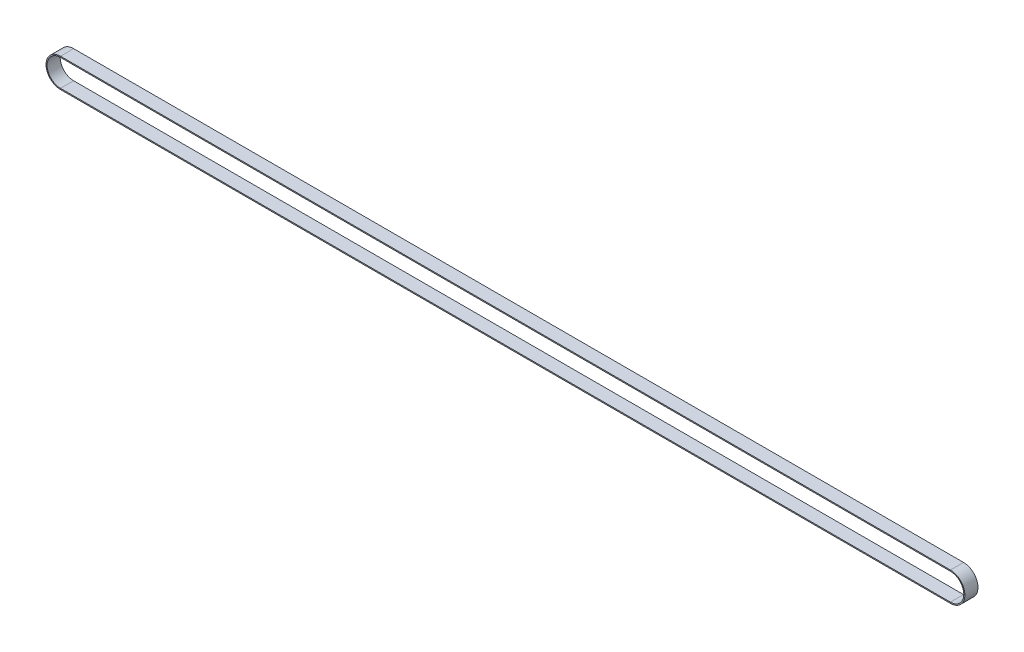
SolidWorks part; units mm, degrees
ref_plane "Plan de face" through (0, 0, 0) normal (0, 0, 1) x (1, 0, 0)
ref_plane "Plan de dessus" through (0, 0, 0) normal (0, 1, 0) x (1, 0, 0)
ref_plane "Plan de droite" through (0, 0, 0) normal (1, 0, 0) x (0, 0, -1)
sketch "Sketch1" plane through (0, 0, 0) normal (0, 0, 1) x (1, 0, 0)
  line L0 (0, 0) -> (1, 0) construction
  line L1 (0, 0) -> (0, 1) construction
  line L2 (-16, 4.9312) -> (390.975, 4.9312)
  line L3 (390.975, -7.2888) -> (-16, -7.2888)
  arc A0 (-16, -7.2888) -> (-16, 4.9312) centre (-16, -1.1788) cw
  arc A1 (390.975, 4.9312) -> (390.975, -7.2888) centre (390.975, -1.1788) cw
ref_plane "Plane1" through (-16, 0, 0) normal (1, 0, 0) x (0, 0, -1)
sketch "Sketch2" plane through (-16, 0, 0) normal (1, 0, 0) x (0, 0, -1)
  line L0 (3, 5.4312) -> (3, 4.9312)
  line L1 (3, 5.4312) -> (-3, 5.4312)
  line L2 (3, 4.9312) -> (-3, 4.9312)
  line L3 (-3, 5.4312) -> (-3, 4.9312)
  point P0 (0, 4.9312)
  dimension "D1" = 6
  dimension "D2" = 0.5
sweep "Sweep1" add profiles "Sketch2" path "Sketch1"
